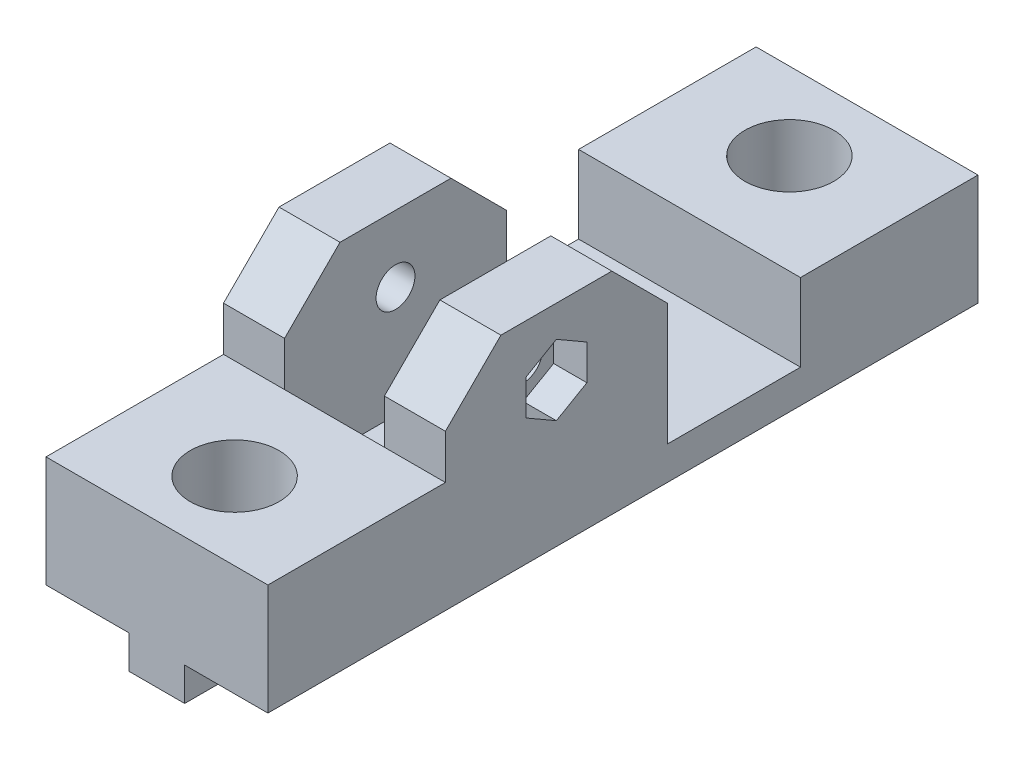
SolidWorks part; units mm, degrees
ref_plane "Front Plane" through (0, 0, 0) normal (0, 0, 1) x (1, 0, 0)
ref_plane "Top Plane" through (0, 0, 0) normal (0, 1, 0) x (1, 0, 0)
ref_plane "Right Plane" through (0, 0, 0) normal (1, 0, 0) x (0, 0, -1)
sketch "Sketch1" plane through (0, 0, 0) normal (0, 1, 0) x (1, 0, 0)
  line L1 (-10, -15) -> (10, -15)
  line L2 (-10, -15) -> (-10, 15)
  line L3 (-10, 15) -> (10, 15)
  line L4 (10, -15) -> (10, 15)
  line L5 (-10, -15) -> (10, 15) construction
  line L6 (-10, 15) -> (10, -15) construction
  point P0 (0, 0)
  dimension "D1" = 20
  dimension "D2" = 30
extrude "Boss-Extrude1" add sketch "Sketch1" along normal blind 3
sketch "Sketch2" plane through (0, 0, 0) normal (0, -1, 0) x (1, 0, 0)
  line L0 (10, -15) -> (-10, -15) construction
  line L1 (-2.5, -15) -> (2.5, -15)
  line L2 (-2.5, -15) -> (-2.5, -3)
  line L3 (-2.5, -3) -> (2.5, -3)
  line L4 (2.5, -15) -> (2.5, -3)
  line L5 (-2.5, -15) -> (2.5, -3) construction
  line L6 (-2.5, -3) -> (2.5, -15) construction
  point P0 (0, -9)
  dimension "D1" = 0
  dimension "D2" = 5
  dimension "D3" = 0
  dimension "D4" = 12
extrude "Boss-Extrude2" add sketch "Sketch2" along normal blind 3
sketch "Sketch3" plane through (0, 3, 0) normal (0, 1, 0) x (1, 0, 0)
  line L0 (10, 15) -> (-10, 15) construction
  circle A0 centre (0, 8) radius 4
  circle A1 centre (0, 8) radius 7
  dimension "D1" = 14
  dimension "D2" = 7
  dimension "D3" = 8
extrude "Boss-Extrude3" add sketch "Sketch3" along normal blind 7
sketch "Sketch4" plane through (0, 3, 0) normal (0, 1, 0) x (1, 0, 0)
  circle A1 centre (0, 8) radius 4
  circle A2 centre (0, 8) radius 4
  dimension "D1" = 0
extrude "Boss-Extrude4" add sketch "Sketch4" along normal blind 1
sketch "Sketch5" plane through (0, 3, 0) normal (0, 1, 0) x (1, 0, 0)
  line L0 (-10, -15) -> (10, -15) construction
  circle A0 centre (0, -8.5) radius 3
  point P4 (0, 0)
  point P7 (-0.7919, -3)
  dimension "D1" = 6
  dimension "D2" = 6.5
  dimension "D3" = 0
extrude "Cut-Extrude1" cut sketch "Sketch5" against normal through all both and the other way through all
chamfer "Chamfer1" [suppressed] distance 4 angle 45
sketch "Sketch6" plane through (0, 3, 0) normal (0, 1, 0) x (1, 0, 0)
  line L0 (10, -15) -> (10, 15) construction
  line L1 (-10, 15) -> (10, 15)
  line L2 (-10, 15) -> (-10, -1)
  line L3 (-10, -1) -> (10, -1)
  line L4 (10, 15) -> (10, -1)
  circle A0 centre (0, 8) radius 7 construction
  circle A1 centre (0, 8) radius 7
  circle A3 centre (0, 8) radius 4
  circle A4 centre (0, 8) radius 4
  line M6 (10, 15) -> (0, 15)
  circle M7 centre (0, 8) radius 7
  line M8 (0, 15) -> (-10, 15)
  line M9 (-10, 15) -> (-10, -15)
  line M11 (10, -15) -> (10, 15)
  dimension "D1" = 16
  dimension "D2" = 0
extrude "Boss-Extrude6" add sketch "Sketch6" along normal up to surface (7 mm away) contours A4 M7 | L3 M9 M11 M6 M7 M8 up to face at (0, 10, -1)
ref_plane "Plane1" through (0, 0, -8) normal (0, 0, 1) x (1, 0, 0)
ref_plane "Plane2" through (0, 0, 17) normal (0, 0, 1) x (1, 0, 0)
sketch "Sketch7" plane through (0, 0, 15) normal (0, 0, 1) x (1, 0, 0)
  line L4 (-10, 0) -> (10, 0)
  line L5 (10, 0) -> (10, 3)
  line L6 (10, 3) -> (-10, 3)
  line L7 (-10, 3) -> (-10, 0)
  line L8 (-10, 0) -> (10, 0)
  line L9 (10, 0) -> (10, 3)
  line L10 (10, 3) -> (-10, 3)
  line L11 (-10, 3) -> (-10, 0)
  dimension "D1" = 0
extrude "Boss-Extrude7" add sketch "Sketch7" along normal blind 19
mirror "Mirror3" about plane through (0, 0, 17) normal (0, 0, 1) of "Boss-Extrude6", "Boss-Extrude4", "Boss-Extrude3", "Boss-Extrude2", "Boss-Extrude1"
sketch "Sketch8" plane through (0, 0, 37) normal (0, 0, -1) x (-1, 0, 0)
  line L4 (2.5, 0) -> (-2.5, 0)
  line L5 (-2.5, 0) -> (-2.5, -3)
  line L6 (-2.5, -3) -> (2.5, -3)
  line L7 (2.5, -3) -> (2.5, 0)
  line L8 (2.5, 0) -> (-2.5, 0)
  line L9 (-2.5, 0) -> (-2.5, -3)
  line L10 (-2.5, -3) -> (2.5, -3)
  line L11 (2.5, -3) -> (2.5, 0)
  dimension "D1" = 0
extrude "Boss-Extrude8" add sketch "Sketch8" along normal blind 12
sketch "Sketch10" plane through (0, 3, 0) normal (0, 1, 0) x (1, 0, 0)
  line L0 (-10, -33) -> (10, -33) construction
  line L1 (4.5, -13) -> (-4.5, -13)
  line L2 (4.5, -13) -> (4.5, -33)
  line L3 (4.5, -33) -> (-4.5, -33)
  line L4 (-4.5, -13) -> (-4.5, -33)
  line L5 (4.5, -13) -> (-4.5, -33) construction
  line L6 (4.5, -33) -> (-4.5, -13) construction
  line L8 (-10, -1) -> (-10, -33) construction
  line L9 (-4.5, -13) -> (-10, -13)
  line L10 (-4.5, -13) -> (-4.5, -33)
  line L11 (-4.5, -33) -> (-10, -33)
  line L12 (-10, -13) -> (-10, -33)
  line L14 (4.5, -13) -> (10, -13)
  line L15 (4.5, -13) -> (4.5, -33)
  line L16 (4.5, -33) -> (10, -33)
  line L17 (10, -13) -> (10, -33)
  circle A0 centre (0, -8.5) radius 3 construction
  circle A1 centre (0, -8.5) radius 3
  circle A2 centre (0, -8.5) radius 6
  point P0 (0, -23)
  line M15 (-10, -1) -> (-10, -33)
  line M16 (-10, -33) -> (10, -33)
  line M17 (10, -33) -> (10, -1)
  dimension "D4" = 12
  dimension "D1" = 0
  dimension "D2" = 20
  dimension "D3" = 9
extrude "Boss-Extrude9" add sketch "Sketch10" along normal blind 16 contours L4 L9 M15 M16 | L14 L2 M16 M17
sketch "Sketch11" plane through (-10, 0, 0) normal (-1, 0, 0) x (0, 0, 1)
  line L0 (17, -11) -> (17, 11) construction
  circle A0 centre (23, 13) radius 1.75
  dimension "D3" = 3.5
  dimension "D1" = 6
  dimension "D2" = 10
extrude "Cut-Extrude2" cut sketch "Sketch11" against normal through all both and the other way through all
sketch "Sketch12" plane through (-10, 0, 0) normal (-1, 0, 0) x (0, 0, 1)
  circle A0 centre (23, 13) radius 1.75 construction
  circle A1 centre (23, 13) radius 1.75
  circle A2 centre (23, 13) radius 3
  dimension "D1" = 6
extrude "Cut-Extrude3" cut sketch "Sketch12" against normal blind 3
sketch "Sketch13" plane through (10, 0, 0) normal (1, 0, 0) x (0, 0, -1)
  line L1 (-23, 16.1754) -> (-25.75, 14.5877)
  line L2 (-25.75, 14.5877) -> (-25.75, 11.4123)
  line L3 (-25.75, 11.4123) -> (-23, 9.8246)
  line L4 (-23, 9.8246) -> (-20.25, 11.4123)
  line L5 (-20.25, 11.4123) -> (-20.25, 14.5877)
  line L6 (-20.25, 14.5877) -> (-23, 16.1754)
  circle A0 centre (-23, 13) radius 1.75 construction
  circle A1 centre (-23, 13) radius 1.75
  circle A2 centre (-23, 13) radius 2.75 construction
  dimension "D1" = 5.5
extrude "Cut-Extrude4" cut sketch "Sketch13" against normal blind 3
chamfer "Chamfer2" distance 5 angle 45 4 edges at (7.25, 19, 13) (7.25, 19, 33) (-7.25, 19, 33) (-7.25, 19, 13)
